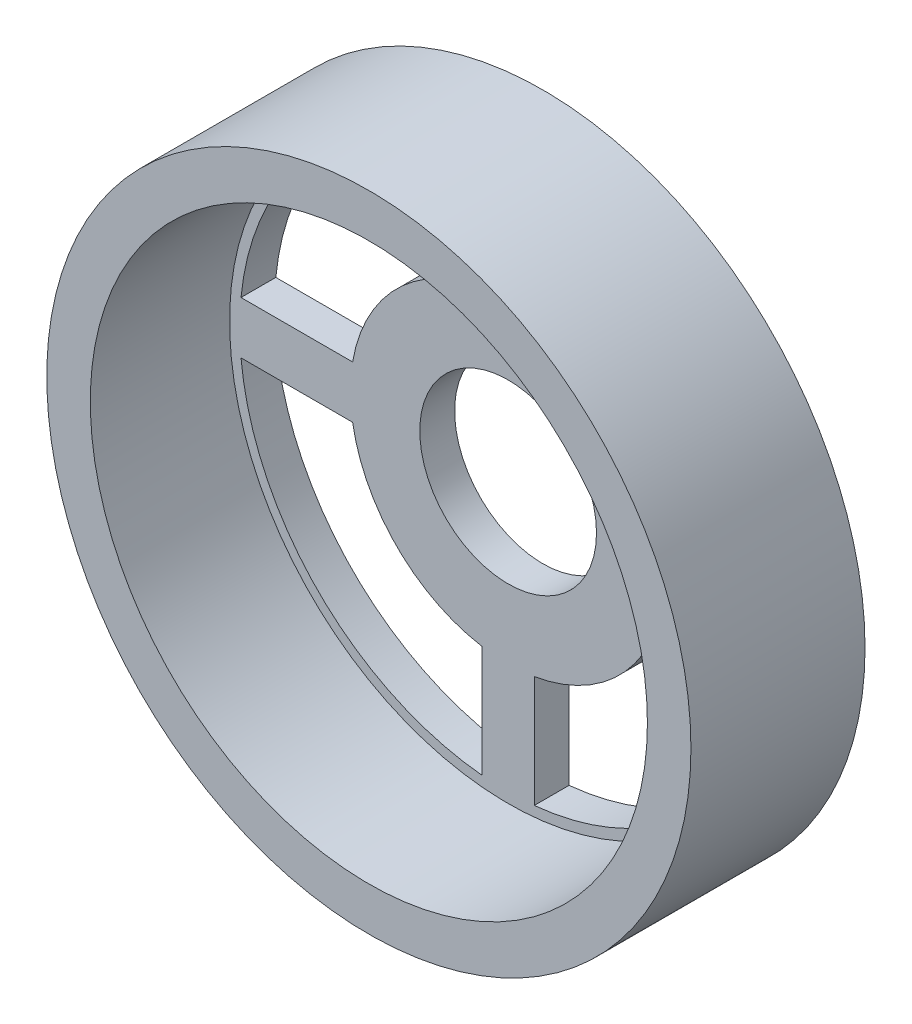
SolidWorks part; units mm, degrees
ref_plane "Plano frontal" through (0, 0, 0) normal (0, 0, 1) x (1, 0, 0)
ref_plane "Plano superior" through (0, 0, 0) normal (0, 1, 0) x (1, 0, 0)
ref_plane "Plano direito" through (0, 0, 0) normal (1, 0, 0) x (0, 0, -1)
sketch "Esboço1" plane through (0, 0, 0) normal (0, 0, 1) x (1, 0, 0)
  circle A0 centre (0, 0) radius 16
  circle A1 centre (0, 0) radius 5.075
  dimension "D1" = 32
  dimension "D2" = 10.15
extrude "Ressalto-extrusão1" add sketch "Esboço1" along normal blind 2
sketch "Esboço2" plane through (0, 0, 0) normal (0, 0, 1) x (1, 0, 0)
  circle A0 centre (0, 0) radius 18
  circle A1 centre (0, 0) radius 16
  dimension "D1" = 36
extrude "Ressalto-extrusão2" add sketch "Esboço2" along normal blind 10
sketch "Esboço3" plane through (0, 0, 0) normal (0, 0, -1) x (-1, 0, 0)
  line L0 (8.9322, 0) -> (15.4175, 0) construction
  line L1 (8.9322, 0) -> (9.0573, 0)
  line L2 (-8.9322, 0) -> (-9.0573, 0)
  line L3 (15.385, 1) -> (15.4175, 1)
  line L4 (8.9322, -1) -> (9.0019, -1)
  line L5 (-8.9322, 0) -> (-15.4175, 0) construction
  line L6 (-8.9322, -1.5) -> (-15.4175, -1.5)
  line L7 (-1.5, 8.9322) -> (-1.5, 15.4175)
  line L8 (8.9322, 1.5) -> (15.4175, 1.5)
  line L9 (1.5, -8.9322) -> (1.5, -15.4175)
  line L10 (-8.9322, 1.5) -> (-15.4175, 1.5)
  line L11 (1.5, 8.9322) -> (1.5, 15.4175)
  line L12 (8.9322, -1.5) -> (15.4175, -1.5)
  line L13 (-1.5, -8.9322) -> (-1.5, -15.4175)
  line L15 (15.385, -1) -> (15.4175, -1)
  line L16 (8.9322, -1) -> (15.4175, -1) construction
  arc A1 (1.5, -15.3443) -> (15.3443, -1.5) centre (0, 0) ccw
  arc A2 (1.5, -8.9322) -> (8.9322, -1.5) centre (0, 0) ccw
  arc A3 (-1.5, 8.9322) -> (-9.0573, 0) centre (0, 0) ccw
  arc A4 (-1.5, 15.3443) -> (-15.3443, 1.5) centre (0, 0) ccw
  arc A5 (15.3443, 1.5) -> (1.5, 15.3443) centre (0, 0) ccw
  arc A6 (8.9322, 1.5) -> (1.5, 8.9322) centre (0, 0) ccw
  arc A7 (-8.9322, -1.5) -> (-1.5, -8.9322) centre (0, 0) ccw
  arc A8 (-15.3443, -1.5) -> (-1.5, -15.3443) centre (0, 0) ccw
  dimension "D1" = 1
  dimension "D3" = 1.5
  dimension "D4" = 1.5
extrude "Corte-extrusão1" cut sketch "Esboço3" against normal blind 10 contours L6 A8 L13 A7 | A2 L9 A1 L12 | A6 L8 A5 L11 | L7 A4 L10 A3
sketch "Esboço4" plane through (0, 0, 10) normal (0, 0, 1) x (1, 0, 0)
  circle A2 centre (0, 0) radius 18.5
  circle A3 centre (0, 0) radius 18.5
  circle A4 centre (0, 0) radius 18 construction
  circle A5 centre (0, 0) radius 18
  dimension "D1" = 0.5
extrude "Ressalto-extrusão3" add sketch "Esboço4" against normal blind 10
